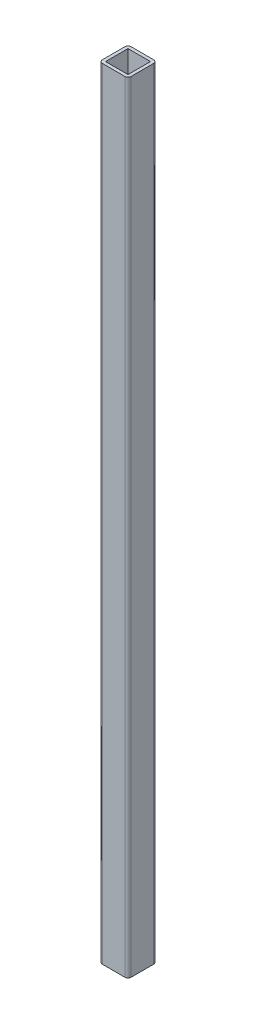
SolidWorks part; units mm, degrees
material "Plain Carbon Steel"
ref_plane "Front Plane" through (0, 0, 0) normal (0, 0, 1) x (1, 0, 0)
ref_plane "Top Plane" through (0, 0, 0) normal (0, 1, 0) x (1, 0, 0)
ref_plane "Right Plane" through (0, 0, 0) normal (1, 0, 0) x (0, 0, -1)
sketch "Sketch1" plane through (0, 0, 0) normal (0, 1, 0) x (1, 0, 0)
  line L1 (2.8, 0) -> (22.8, 0)
  line L2 (0, -2.8) -> (0, -22.8)
  line L3 (2.8, -25.6) -> (22.8, -25.6)
  line L4 (25.6, -2.8) -> (25.6, -22.8)
  arc A0 (22.8, 0) -> (25.6, -2.8) centre (22.8, -2.8) cw
  arc A1 (22.8, -25.6) -> (25.6, -22.8) centre (22.8, -22.8) ccw
  arc A2 (0, -22.8) -> (2.8, -25.6) centre (2.8, -22.8) ccw
  arc A3 (2.8, 0) -> (0, -2.8) centre (2.8, -2.8) ccw
  point P7 (25.6, 0)
  point P10 (25.6, -25.6)
  point P15 (0, 0)
  dimension "D2" = 2.8
  dimension "D1" = 25.6
extrude "Boss-Extrude1" add sketch "Sketch1" along normal blind 693
sketch "Sketch3" plane through (0, 0, 0) normal (0, -1, 0) x (-1, 0, 0)
  line L4 (-2.8, -2.8) -> (-22.8, -2.8)
  line L5 (-2.8, -2.8) -> (-2.8, -22.8)
  line L6 (-2.8, -22.8) -> (-22.8, -22.8)
  line L7 (-22.8, -2.8) -> (-22.8, -22.8)
  line L8 (-2.8, -2.8) -> (-22.8, -22.8) construction
  line L9 (-2.8, -22.8) -> (-22.8, -2.8) construction
  point P6 (-12.8, -12.8)
extrude "Cut-Extrude1" cut sketch "Sketch3" against normal blind 693
